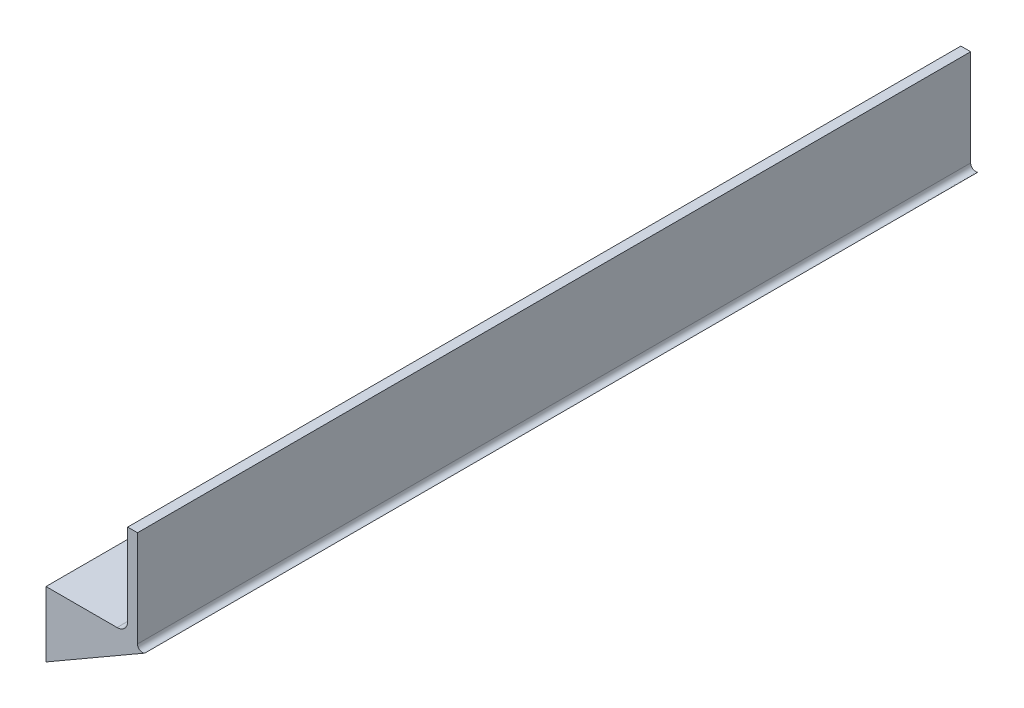
SolidWorks part; units mm, degrees
ref_plane "Alzado" through (0, 0, 0) normal (0, 0, 1) x (1, 0, 0)
ref_plane "Planta" through (0, 0, 0) normal (0, 1, 0) x (1, 0, 0)
ref_plane "Vista lateral" through (0, 0, 0) normal (1, 0, 0) x (0, 0, -1)
sketch "Croquis2" plane through (0, 0, 0) normal (0, 0, 1) x (1, 0, 0)
  line L0 (0, 0) -> (21.75, 0)
  line L1 (25, 3.25) -> (25, 28.25)
  line L4 (25, 28.25) -> (28, 28.25)
  line L5 (28, 28.25) -> (28, -1.2361)
  line L6 (0, 0) -> (0, -20)
  line L8 (28, -3.8342) -> (0, -20)
  line L9 (28, -3.8342) -> (0, -3.8342) construction
  line L10 (28, -3.8342) -> (30.25, -2.5352)
  arc A0 (21.75, 0) -> (25, 3.25) centre (21.75, 3.25) ccw
  arc A1 (28, -1.2361) -> (30.25, -2.5352) centre (29.5, -1.2361) ccw
  point P1 (30.3811, -0.4309)
  dimension "D1" = 6.5
  dimension "D7" = 3
  dimension "D2" = 3
  dimension "D3" = 25
  dimension "D4" = 30
  dimension "D5" = 25
  dimension "D6" = 20
extrude "Saliente-Extruir1" add sketch "Croquis2" along normal blind 255
sketch "Croquis3" plane through (0, 0, 0) normal (0, 1, 0) x (1, 0, 0)
  line L0 (14.75, 0) -> (14.75, -255) construction
  line L1 (21.75, 0) -> (0, 0) construction
  line L2 (21.75, -255) -> (0, -255) construction
  line L3 (21.75, -255) -> (21.75, 0) construction
  circle A0 centre (14.75, -198.5) radius 3
  circle A1 centre (14.75, -56.5) radius 3
  point P12 (14.75, -127.5)
  dimension "D2" = 6
  dimension "D3" = 6
  dimension "D1" = 7
  dimension "D4" = 142
  dimension "D5" = 71
sketch "Croquis4" plane through (0, 0, 0) normal (-1, 0, 0) x (0, 0, 1)
  line L0 (0, -13) -> (255, -13) construction
  line L3 (255, -20) -> (0, -20) construction
  text T0 "<b>BIOBIZKAIA</b>" font "Century Gothic" height in points 28
  point P7 (0, 0)
  dimension "D1" = 7
extrude "Cortar-Extruir1" cut sketch "Croquis4" against normal blind 1
extrude "Cortar-Extruir2" cut sketch "Croquis3" against normal blind 4
